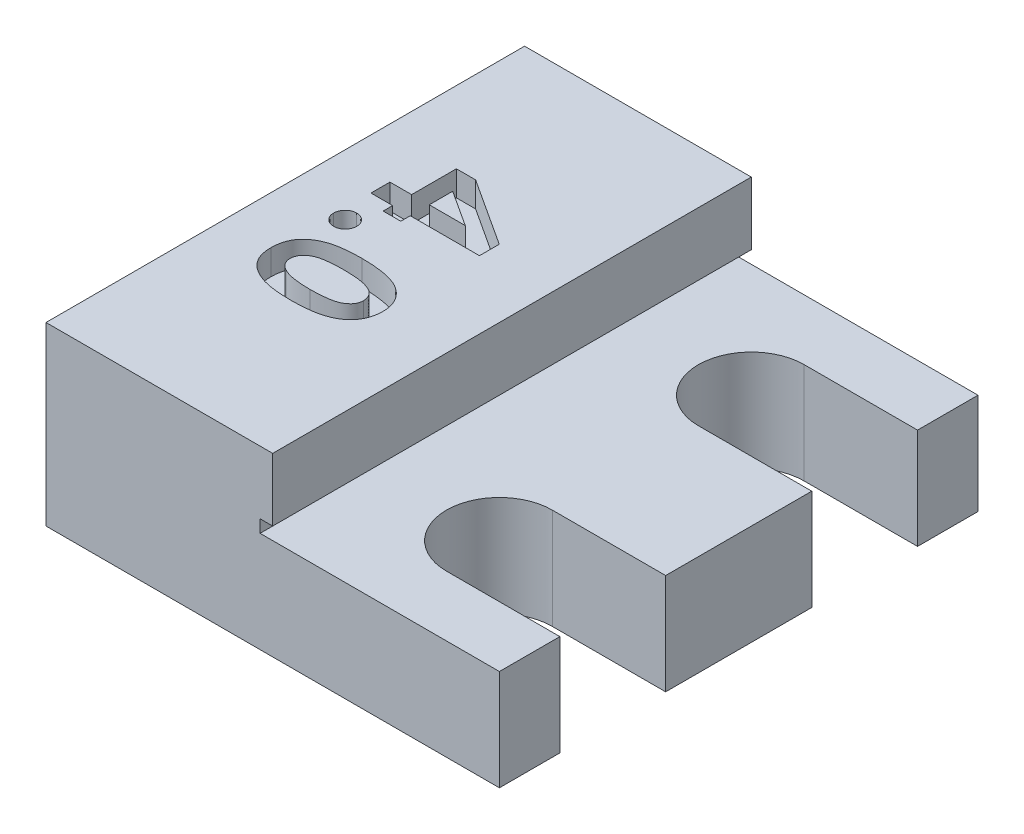
SolidWorks part; units mm, degrees
ref_plane "Front Plane" through (0, 0, 0) normal (0, 0, 1) x (1, 0, 0)
ref_plane "Top Plane" through (0, 0, 0) normal (0, 1, 0) x (1, 0, 0)
ref_plane "Right Plane" through (0, 0, 0) normal (1, 0, 0) x (0, 0, -1)
sketch "Sketch1" plane through (0, 0, 0) normal (0, 0, 1) x (1, 0, 0)
  line L1 (0, 0) -> (18, 0)
  line L2 (0, 0) -> (0, 7)
  line L7 (18, 4) -> (9, 4)
  line L8 (9, 4.5) -> (9, 7)
  line L9 (9, 7) -> (0, 7)
  line L10 (18, 4) -> (18, 0)
  line L11 (9, 4) -> (8.5, 4)
  line L12 (8.5, 4) -> (8.5, 4.5)
  line L13 (8.5, 4.5) -> (9, 4.5)
  dimension "D1" = 18
  dimension "D2" = 4
  dimension "D3" = 9
  dimension "D4" = 0.5
  dimension "D5" = 0.5
  dimension "D6" = 7
extrude "Boss-Extrude1" add sketch "Sketch1" along normal blind 19
sketch "Sketch2" plane through (0, 7, 0) normal (0, 1, 0) x (1, 0, 0)
  line L0 (18, -9.5) -> (0, -9.5) construction
  line L2 (0, -19) -> (0, 0) construction
  line L3 (13.5, -4.5) -> (13.5, -14.5) construction
  line L4 (13.5, -2.4) -> (18, -2.4)
  line L5 (13.5, -6.6) -> (18, -6.6)
  line L6 (18, -6.6) -> (18, -2.4)
  line L7 (13.5, -12.4) -> (18, -12.4)
  line L8 (18, -12.4) -> (18, -16.6)
  line L9 (18, -16.6) -> (13.5, -16.6)
  line L10 (9, -19) -> (9, 0) construction
  line L11 (18, -19) -> (18, 0) construction
  arc A0 (13.5, -2.4) -> (13.5, -6.6) centre (13.5, -4.5) ccw
  arc A1 (13.5, -12.4) -> (13.5, -16.6) centre (13.5, -14.5) ccw
  point P8 (13.5, -9.5)
  dimension "D2" = 4.2
  dimension "D1" = 10
  dimension "D3" = 4.5
extrude "Cut-Extrude1" cut sketch "Sketch2" against normal through all
sketch "Sketch3" plane through (0, 7, 0) normal (0, 1, 0) x (1, 0, 0)
  line L0 (2, 0) -> (2, -19) construction
  line L1 (9, 0) -> (0, 0) construction
  line L2 (9, -19) -> (0, -19) construction
  line L3 (0, -19) -> (0, 0) construction
  text T0 "4.0" font "Century Gothic" height 4.2
  dimension "D1" = 2
extrude "Cut-Extrude2" cut sketch "Sketch3" against normal blind 1
sketch "Sketch4" plane through (0, 0, 0) normal (0, -1, 0) x (1, 0, 0)
  line L0 (9, 19) -> (9, 0) construction
  line L1 (9, 19) -> (9, 0)
  line L3 (9, 9.5) -> (0, 9.5) construction
  line L4 (0, 19) -> (0, 0) construction
  line L5 (0, 19) -> (18, 19) construction
  line L6 (7.5, 1.5) -> (1.5, 1.5)
  line L7 (7.5, 1.5) -> (7.5, 17.5)
  line L8 (7.5, 17.5) -> (1.5, 17.5)
  line L9 (1.5, 1.5) -> (1.5, 17.5)
  line L10 (7.5, 1.5) -> (1.5, 17.5) construction
  line L11 (7.5, 17.5) -> (1.5, 1.5) construction
  point P6 (4.5, 9.5)
  dimension "D1" = 1.5
  dimension "D2" = 1.5
extrude "Cut-Extrude3" cut sketch "Sketch4" against normal offset from surface (5 mm away) 1 contours L9 L6 L7 L8 up to face at (3.8567, 6, 12.0456)
